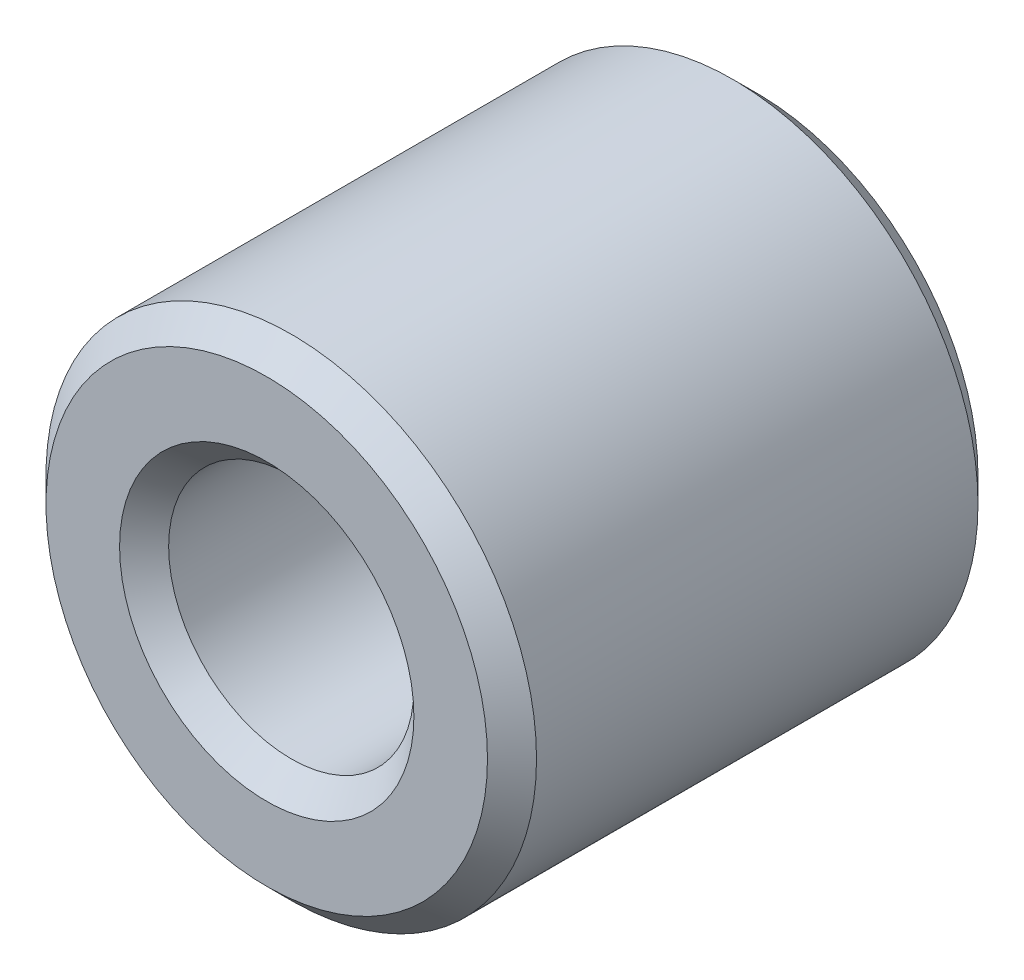
SolidWorks part; units mm, degrees
ref_plane "Alzado" through (0, 0, 0) normal (0, 0, 1) x (1, 0, 0)
ref_plane "Planta" through (0, 0, 0) normal (0, 1, 0) x (1, 0, 0)
ref_plane "Vista lateral" through (0, 0, 0) normal (1, 0, 0) x (0, 0, -1)
sketch "Croquis1" plane through (0, 0, 0) normal (0, 0, 1) x (1, 0, 0)
  circle A0 centre (0, 0) radius 3
  circle A1 centre (0, 0) radius 1.5
  dimension "D1" = 3
  dimension "D2" = 6
extrude "Saliente-Extruir1" add sketch "Croquis1" along normal blind 6
chamfer "Chaflán1" distance 0.3 angle 45 4 edges at (1.5, 0, 0) (3, 0, 0) (3, 0, 6) (1.5, 0, 6)
